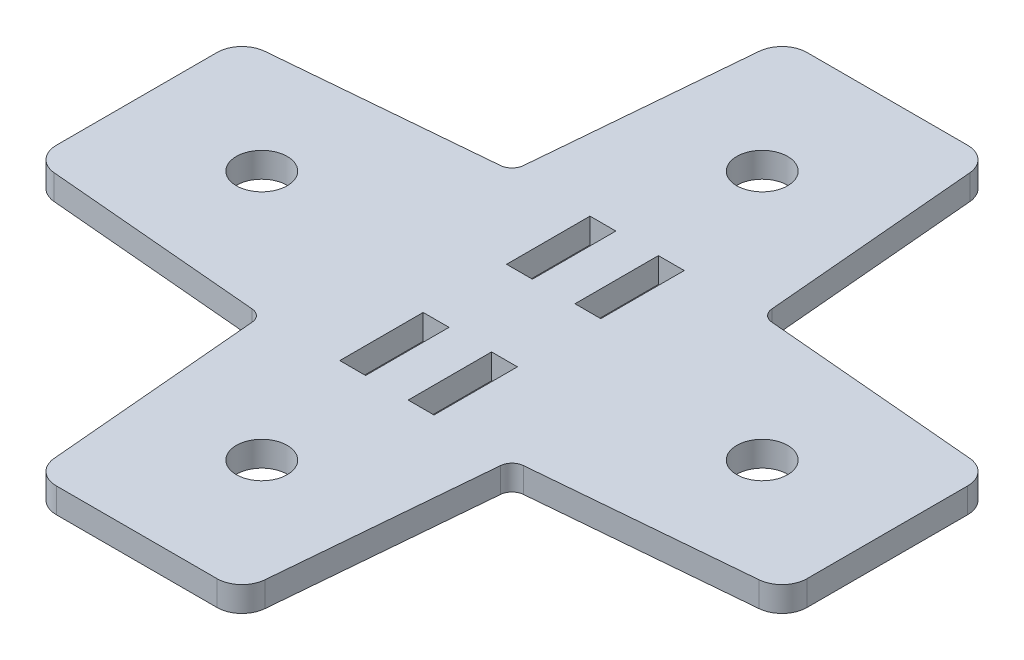
SolidWorks part; units mm, degrees
ref_plane "Front Plane" through (0, 0, 0) normal (0, 0, 1) x (1, 0, 0)
ref_plane "Top Plane" through (0, 0, 0) normal (0, 1, 0) x (1, 0, 0)
ref_plane "Right Plane" through (0, 0, 0) normal (1, 0, 0) x (0, 0, -1)
sketch "Sketch1" plane through (0, 0, 0) normal (0, 1, 0) x (1, 0, 0)
  line L0 (0, 0) -> (0, 45) construction
  line L1 (0, 0) -> (0, -45) construction
  line L2 (-45, 0) -> (45, 0) construction
  line L3 (45, -45) -> (-45, -45) construction
  line L4 (45, -45) -> (45, 45) construction
  line L5 (45, 45) -> (-45, 45) construction
  line L6 (-45, -45) -> (-45, 45) construction
  line L7 (45, -45) -> (-45, 45) construction
  line L8 (45, 45) -> (-45, -45) construction
  line L9 (-14.715, 18.261) -> (-12.62, 42.261) construction
  line L10 (-45, 15) -> (45, 15) construction
  line L11 (-14.8902, 16.2541) -> (-12.62, 42.2609)
  line L12 (14.715, 18.261) -> (12.62, 42.261) construction
  line L13 (14.8902, 16.2541) -> (12.62, 42.2609)
  line L14 (14.715, -18.261) -> (12.62, -42.261) construction
  line L15 (-14.715, -18.261) -> (-12.62, -42.261) construction
  line L16 (9.6314, -45) -> (-9.6314, -45)
  line L17 (14.8902, -16.2541) -> (12.62, -42.2609)
  line L18 (-14.8902, -16.2541) -> (-12.62, -42.2609)
  line L19 (18.261, -14.715) -> (42.261, -12.62) construction
  line L20 (16.2541, -14.8902) -> (42.2609, -12.62)
  line L21 (-18.261, 14.715) -> (-42.261, 12.62) construction
  line L22 (9.6314, 45) -> (-9.6314, 45)
  line L23 (-16.2541, 14.8902) -> (-42.2609, 12.62)
  line L24 (-18.261, -14.715) -> (-42.261, -12.62) construction
  line L25 (-16.2541, -14.8902) -> (-42.2609, -12.62)
  line L26 (18.261, 14.715) -> (42.261, 12.62) construction
  line L27 (16.2541, 14.8902) -> (42.2609, 12.62)
  line L28 (-45, 9.6314) -> (-45, -9.6314)
  line L29 (45, 9.6314) -> (45, -9.6314)
  line L30 (-45, 30) -> (45, 30) construction
  line L31 (2.55, 0) -> (2.55, 45) construction
  line L32 (-2.55, 0) -> (-2.55, 45) construction
  line L33 (-2.55, 15) -> (-2.55, 5)
  line L34 (-2.55, 5) -> (-5.65, 5)
  line L35 (-5.65, 5) -> (-5.65, 15)
  line L36 (-5.65, 15) -> (-2.55, 15)
  line L37 (5.65, 15) -> (2.55, 15)
  line L38 (5.65, 5) -> (5.65, 15)
  line L39 (2.55, 5) -> (5.65, 5)
  line L40 (2.55, 15) -> (2.55, 5)
  line L41 (2.55, -15) -> (2.55, -5)
  line L42 (2.55, -5) -> (5.65, -5)
  line L43 (5.65, -5) -> (5.65, -15)
  line L44 (5.65, -15) -> (2.55, -15)
  line L45 (-5.65, -15) -> (-2.55, -15)
  line L46 (-5.65, -5) -> (-5.65, -15)
  line L47 (-2.55, -5) -> (-5.65, -5)
  line L48 (-2.55, -15) -> (-2.55, -5)
  arc A0 (12.62, 42.2609) -> (9.6314, 45) centre (9.6314, 42) ccw
  arc A1 (-12.62, -42.2609) -> (-9.6314, -45) centre (-9.6314, -42) ccw
  arc A2 (12.62, -42.2609) -> (9.6314, -45) centre (9.6314, -42) cw
  arc A3 (42.2609, -12.62) -> (45, -9.6314) centre (42, -9.6314) ccw
  arc A4 (-42.2609, 12.62) -> (-45, 9.6314) centre (-42, 9.6314) ccw
  arc A5 (-42.2609, -12.62) -> (-45, -9.6314) centre (-42, -9.6314) cw
  arc A6 (42.2609, 12.62) -> (45, 9.6314) centre (42, 9.6314) cw
  arc A7 (-12.62, 42.2609) -> (-9.6314, 45) centre (-9.6314, 42) cw
  arc A8 (14.8902, 16.2541) -> (16.2541, 14.8902) centre (16.3845, 16.3845) ccw
  arc A9 (16.2541, -14.8902) -> (14.8902, -16.2541) centre (16.3845, -16.3845) ccw
  arc A10 (-14.8902, -16.2541) -> (-16.2541, -14.8902) centre (-16.3845, -16.3845) ccw
  arc A11 (-16.2541, 14.8902) -> (-14.8902, 16.2541) centre (-16.3845, 16.3845) ccw
  point P22 (12.3809, 45)
  point P35 (-12.3809, -45)
  point P36 (12.3809, -45)
  point P42 (45, -12.3809)
  point P48 (-45, 12.3809)
  point P53 (-12.3809, 45)
  point P57 (-45, -12.3809)
  point P63 (45, 12.3809)
  point P66 (14.9997, 14.9997)
  point P69 (14.9997, -14.9997)
  point P72 (-14.9997, -14.9997)
  point P75 (-14.9997, 14.9997)
  dimension "D8" = 3
  dimension "D9" = 1.5
  dimension "D1" = 90
  dimension "D2" = 90
  dimension "D3" = 14.715
  dimension "D4" = 12.62
  dimension "D5" = 30
  dimension "D6" = 2.739
  dimension "D7" = 3.261
  dimension "D10" = 30
  dimension "D13" = 3.1
  dimension "D14" = 10
  dimension "D11" = 2.55
  dimension "D12" = 2.55
extrude "Boss-Extrude1" add sketch "Sketch1" along normal blind 3
hole_wizard "Ø6.1 (6.1) Diameter Hole1" positions "Sketch3" profile "Sketch2" hole size "Ø6.1" standard "DIN"
sketch "Sketch3" plane through (0, 3, 0) normal (0, 1, 0) x (1, 0, 0)
  line L1 (0, 45) -> (0, 30) construction
  line L2 (9.6314, 45) -> (-9.6314, 45) construction
  line L4 (-45, 0) -> (-30, 0) construction
  line L5 (-45, 9.6314) -> (-45, -9.6314) construction
  line L7 (45, 0) -> (30, 0) construction
  line L8 (45, -9.6314) -> (45, 9.6314) construction
  line L10 (0, -45) -> (0, -30) construction
  line L11 (-9.6314, -45) -> (9.6314, -45) construction
  point P0 (0, -30)
  point P2 (30, 0)
  point P4 (0, 30)
  point P6 (-30, 0)
  dimension "D1" = 15
sketch "Sketch2" plane through (0, 3, 30) normal (1, 0, 0) x (0, 0, 1)
  line L0 (0, 0) -> (0, 11.8326)
  line L1 (0, 11.8326) -> (3.05, 10)
  line L2 (3.05, 10) -> (3.05, 0)
  line L5 (3.05, 0) -> (0, 0)
  line L10 (0, 11.8326) -> (-3.05, 10) construction
  line L11 (0, -6.35) -> (0, 107.95) construction
  dimension "Hole Dia." = 6.1
  dimension "Hole Depth" = 10
  dimension "Drill Angle" = 118
